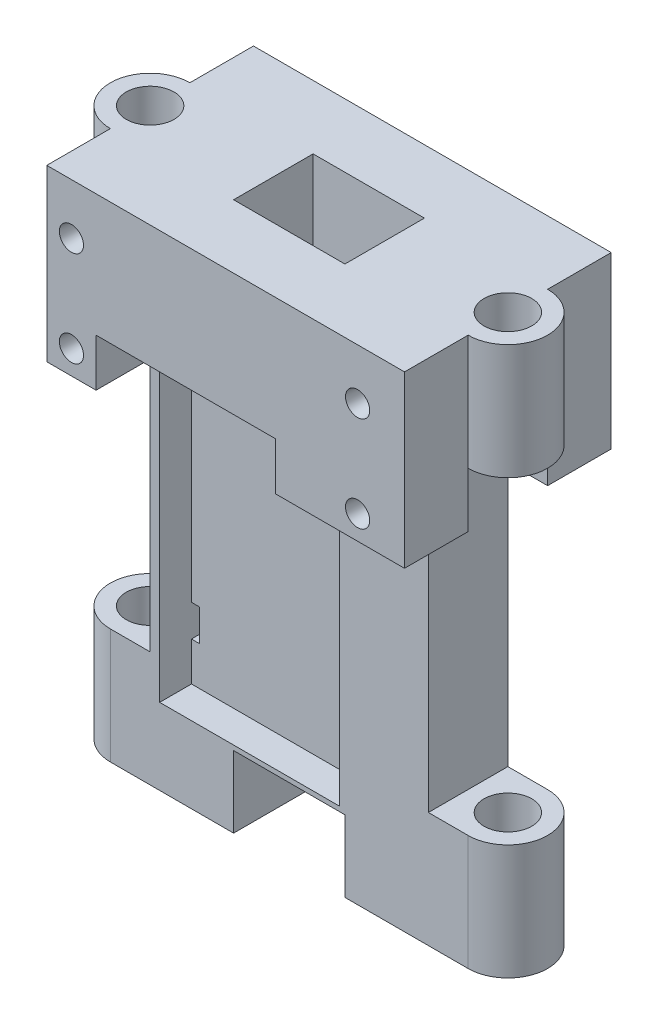
SolidWorks part; units mm, degrees
ref_plane "前视基准面" through (0, 0, 0) normal (0, 0, 1) x (1, 0, 0)
ref_plane "上视基准面" through (0, 0, 0) normal (0, 1, 0) x (1, 0, 0)
ref_plane "右视基准面" through (0, 0, 0) normal (1, 0, 0) x (0, 0, -1)
other "Configuration Table"
sketch "Sketch2" plane through (0, 0, 0) normal (0, 1, 0) x (1, 0, 0)
  line L0 (0, 0) -> (28.575, 0) construction
  line L2 (-28.575, 6.35) -> (28.575, 6.35)
  line L3 (28.575, -6.35) -> (-28.575, -6.35)
  circle A0 centre (28.575, 0) radius 3.81
  arc A1 (28.575, -6.35) -> (28.575, 6.35) centre (28.575, 0) ccw
  circle A2 centre (-28.575, 0) radius 3.81
  arc A3 (-28.575, 6.35) -> (-28.575, -6.35) centre (-28.575, 0) ccw
  dimension "D3" = 7.62
  dimension "D4" = 12.7
  dimension "D5" = 7.62
  dimension "D6" = 12.7
  dimension "D1" = 57.15
  dimension "D2" = 57.15
  dimension "D7" = 12.7
  dimension "D8" = 28.575
extrude "Boss-Extrude1" add sketch "Sketch2" along normal mid plane 87.63
sketch "Sketch7" plane through (0, 0, 6.35) normal (0, 0, 1) x (1, 0, 0)
  line L0 (0, 0) -> (0, 24.257) construction
  line L1 (0, -55) -> (0, 55) construction
  line L2 (0, 24.257) -> (8.001, 24.257) construction
  line L3 (0, 24.257) -> (-20.701, 24.257) construction
  line L5 (-20.701, 24.257) -> (8.001, 24.257)
  line L6 (-20.701, 24.257) -> (-20.701, -31.623)
  line L7 (-20.701, -31.623) -> (8.001, -31.623)
  line L8 (8.001, 24.257) -> (8.001, -31.623)
  dimension "D1" = 24.257
  dimension "D2" = 8.001
  dimension "D3" = 20.701
  dimension "D4" = 55.88
extrude "Cut-Extrude3" cut sketch "Sketch7" against normal blind 5.08
mirror "Mirror1" about plane through (0, 0, 0) normal (0, 0, 1) of "Cut-Extrude3"
sketch "Sketch9" plane through (0, 0, 0) normal (0, 1, 0) x (1, 0, 0)
  circle A0 centre (0, 0) radius 36.576
sketch "Sketch11" plane through (0, 0, -6.35) normal (0, 0, -1) x (-1, 0, 0)
  line L0 (0, 40.2336) -> (0, -40.2336) construction
  line L1 (-28.575, 43.815) -> (28.575, 43.815)
  line L2 (-28.575, 43.815) -> (-28.575, 16.637)
  line L3 (-28.575, 16.637) -> (28.575, 16.637)
  line L4 (28.575, 43.815) -> (28.575, 16.637)
  line L6 (40.2336, 0) -> (-40.2336, 0) construction
  line L7 (-28.575, 43.815) -> (-28.575, -43.815) construction
  line L8 (-28.575, 43.815) -> (28.575, 43.815) construction
  dimension "D2" = 28.575
  dimension "D3" = 16.637
extrude "Boss-Extrude2" add sketch "Sketch11" along normal blind 10.16
mirror "Mirror3" about plane through (0, 0, 0) normal (0, 0, 1) of "Boss-Extrude2"
sketch "Sketch14" plane through (0, 0, -16.51) normal (0, 0, -1) x (-1, 0, 0)
  line L0 (-28.575, 16.637) -> (28.575, 16.637) construction
  line L1 (-8.001, 16.637) -> (20.701, 16.637)
  line L2 (-8.001, 16.637) -> (-8.001, 24.257)
  line L3 (-8.001, 24.257) -> (20.701, 24.257)
  line L4 (20.701, 16.637) -> (20.701, 24.257)
  line L5 (-8.001, -31.623) -> (-8.001, 24.257) construction
  line L6 (0, 40.2336) -> (0, -40.2336) construction
  dimension "D1" = 7.62
  dimension "D2" = 20.701
extrude "Cut-Extrude4" cut sketch "Sketch14" against normal blind 10.16
mirror "Mirror4" about plane through (0, 0, 0) normal (0, 0, 1) of "Cut-Extrude4"
sketch "Sketch15" plane through (0, 43.815, 0) normal (0, 1, 0) x (1, 0, 0)
  line L0 (25.485, 6.35) -> (25.485, 26.2358) construction
  line L1 (28.575, 6.35) -> (-28.575, 6.35) construction
  circle A0 centre (0, 0) radius 36.576
  dimension "D1" = 19.8858
sketch "Sketch16" plane through (0, 43.815, 0) normal (0, 1, 0) x (1, 0, 0)
  line L0 (28.575, 6.35) -> (-28.575, 6.35) construction
  line L7 (-8.89, -6.35) -> (8.89, -6.35)
  line L8 (-8.89, -6.35) -> (-8.89, 6.35)
  line L9 (-8.89, 6.35) -> (8.89, 6.35)
  line L10 (8.89, -6.35) -> (8.89, 6.35)
  line L11 (-8.89, -6.35) -> (8.89, 6.35) construction
  line L12 (-8.89, 6.35) -> (8.89, -6.35) construction
  point P0 (0, 0)
  dimension "D1" = 17.78
extrude "Cut-Extrude5" cut sketch "Sketch16" against normal blind 12.7
sketch "Sketch17" plane through (0, -43.815, 0) normal (0, -1, 0) x (1, 0, 0)
  line L0 (-28.575, 6.35) -> (28.575, 6.35) construction
  line L1 (-8.89, -6.35) -> (8.89, -6.35)
  line L2 (-8.89, -6.35) -> (-8.89, 6.35)
  line L3 (-8.89, 6.35) -> (8.89, 6.35)
  line L4 (8.89, -6.35) -> (8.89, 6.35)
  line L5 (-8.89, -6.35) -> (8.89, 6.35) construction
  line L6 (-8.89, 6.35) -> (8.89, -6.35) construction
  point P0 (0, 0)
  dimension "D1" = 17.78
extrude "Cut-Extrude6" cut sketch "Sketch17" against normal blind 11.43
sketch "Sketch19" plane through (0, 0, 0) normal (0, 1, 0) x (1, 0, 0)
  line L4 (22.225, 6.35) -> (22.225, -6.35)
  line L5 (22.225, -6.35) -> (28.575, -6.35)
  line L6 (28.575, 6.35) -> (22.225, 6.35)
  arc A0 (28.575, 6.35) -> (28.575, -6.35) centre (28.575, 0) cw
extrude "Cut-Extrude7" cut sketch "Sketch19" against normal mid plane 50.8
mirror "Mirror5" about plane through (0, 0, 0) normal (1, 0, 0) of "Cut-Extrude7"
sketch "Sketch21" plane through (0, 0, 1.27) normal (0, 0, 1) x (1, 0, 0)
  line L0 (6.731, 10.16) -> (-20.701, 10.16) construction
  line L1 (8.0842, 0) -> (8.001, 15.24) construction
  line L2 (8.001, 15.24) -> (6.731, 15.24)
  line L3 (8.001, 15.24) -> (8.001, 10.16)
  line L4 (36.576, 0) -> (-36.576, 0) construction
  line L5 (8.001, -31.623) -> (8.001, 24.257) construction
  line L6 (8.001, -31.623) -> (8.001, 16.637) construction
  line L7 (8.001, 10.16) -> (6.731, 10.16)
  line L8 (6.731, 15.24) -> (6.731, 10.16)
  line L9 (-20.701, 24.257) -> (-20.701, -31.623) construction
  line L10 (8.001, 10.16) -> (8.001, -20.32) construction
  line L11 (-20.701, 10.16) -> (-19.431, 10.16)
  line L12 (-20.701, 10.16) -> (-20.701, 15.24)
  line L13 (-20.701, 15.24) -> (-19.431, 15.24)
  line L14 (-19.431, 10.16) -> (-19.431, 15.24)
  line L15 (6.731, -20.32) -> (-20.701, -20.32) construction
  line L16 (8.001, -20.32) -> (6.731, -20.32)
  line L17 (8.001, -20.32) -> (8.001, -25.4)
  line L18 (8.001, -25.4) -> (6.731, -25.4)
  line L19 (6.731, -20.32) -> (6.731, -25.4)
  line L21 (-20.701, -20.32) -> (-19.431, -20.32)
  line L22 (-20.701, -20.32) -> (-20.701, -25.4)
  line L23 (-20.701, -25.4) -> (-19.431, -25.4)
  line L24 (-19.431, -20.32) -> (-19.431, -25.4)
  dimension "D1" = 5.08
  dimension "D2" = 1.27
  dimension "D3" = 5.08
  dimension "D4" = 1.27
  dimension "D5" = 15.24
  dimension "D6" = 30.48
  dimension "D7" = 5.08
  dimension "D8" = 1.27
  dimension "D9" = 1.27
extrude "Cut-Extrude8" cut sketch "Sketch21" against normal through all
sketch "Sketch23" plane through (0, 0, 16.51) normal (0, 0, 1) x (1, 0, 0)
  line L0 (-20.701, 24.257) -> (-28.575, 16.637) construction
  line L1 (21.082, 43.815) -> (21.082, 20.447) construction
  line L2 (-24.638, 20.447) -> (28.575, 20.447) construction
  line L3 (28.575, 43.815) -> (28.575, 16.637) construction
  line L4 (-24.638, 35.687) -> (28.575, 35.687) construction
  line L5 (-24.638, 20.447) -> (-24.638, 43.815) construction
  line L6 (36.576, 43.815) -> (-36.576, 43.815) construction
  circle A4 centre (-24.638, 20.447) radius 1.9304
  circle A5 centre (-24.638, 35.687) radius 1.9304
  circle A6 centre (21.082, 20.447) radius 1.9304
  circle A7 centre (21.082, 35.687) radius 1.9304
  dimension "D3" = 45.72
  dimension "D1" = 3.8608
  dimension "D2" = 15.24
extrude "Cut-Extrude9" cut sketch "Sketch23" against normal blind 11.27 draft 8 contours A6 | A7 | A4 | A5
mirror "Mirror8" about plane through (0, 0, 0) normal (0, 0, 1) of "Cut-Extrude9"
